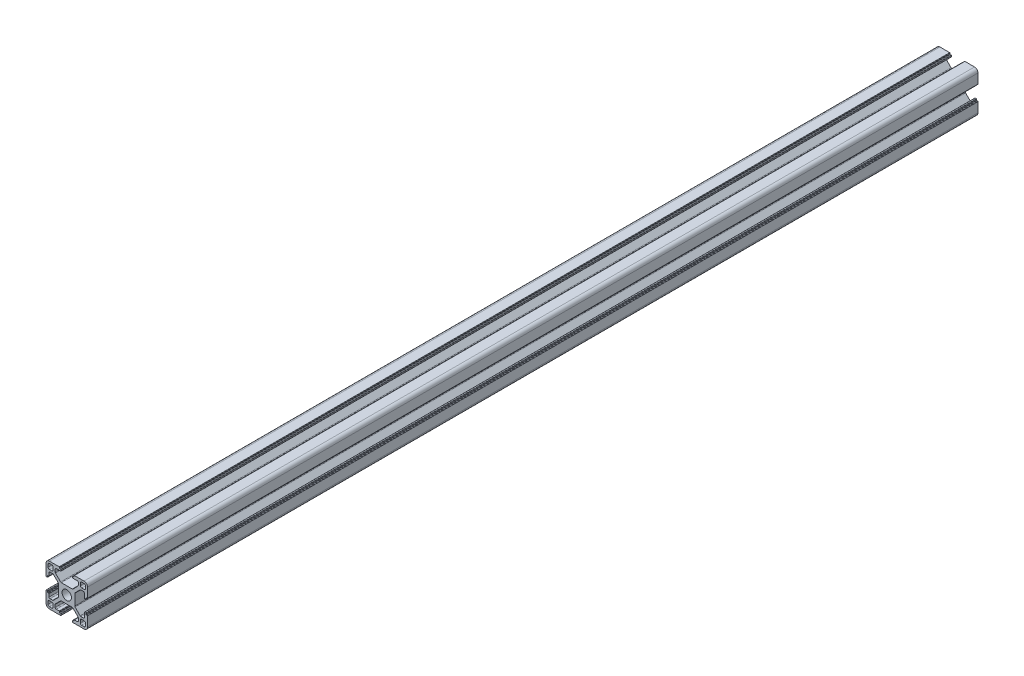
SolidWorks part; units mm, degrees
material "6063-T5"
ref_plane "Front Plane" through (0, 0, 0) normal (0, 0, 1) x (1, 0, 0)
ref_plane "Top Plane" through (0, 0, 0) normal (0, 1, 0) x (1, 0, 0)
ref_plane "Right Plane" through (0, 0, 0) normal (1, 0, 0) x (0, 0, -1)
sketch "Sketch1" plane through (0, 0, 0) normal (0, 0, 1) x (1, 0, 0)
  line L0 (0, 2.5) -> (0, 10.6)
  line L1 (2.5, 30) -> (9.5, 30)
  line L2 (30, 27.5) -> (30, 20.5)
  line L3 (27.5, 0) -> (19.4, 0)
  line L4 (19.464, 9.1128) -> (23.1303, 5.4465)
  line L5 (21.0197, 10.536) -> (24.686, 6.8697)
  line L6 (10.536, 21.0197) -> (6.8697, 24.686)
  line L7 (8.9803, 19.464) -> (5.314, 23.1303)
  line L8 (11.0663, 20.8) -> (18.9337, 20.8)
  line L9 (20.8, 18.9337) -> (20.8, 11.0663)
  line L10 (18.9337, 9.3324) -> (11.0663, 9.3324)
  line L11 (9.2, 11.0663) -> (9.2, 18.9337)
  line L12 (0, 19.4) -> (0, 27.5)
  line L13 (30, 9.5) -> (30, 2.5)
  line L14 (19.4, 27.8) -> (22.6, 27.8)
  line L15 (10.6, 27.8) -> (7.4, 27.8)
  line L16 (10.6, 0) -> (2.5, 0)
  line L17 (2.2, 20.5) -> (2.2, 22.6)
  line L18 (2.2, 9.5) -> (2.2, 7.4)
  line L19 (9.5, 2.3324) -> (7.4, 2.3324)
  line L20 (19.464, 21.0197) -> (23.1303, 24.686)
  line L21 (21.0197, 19.464) -> (24.686, 23.1303)
  line L22 (8.9803, 10.536) -> (5.314, 6.8697)
  line L23 (10.536, 9.1128) -> (6.8697, 5.4465)
  line L24 (10.8, 28.8) -> (10.8, 28)
  line L25 (19.2, 28.8) -> (19.2, 28)
  line L26 (0.2, 19.2) -> (1, 19.2)
  line L27 (0.2, 10.8) -> (1, 10.8)
  line L28 (28.8, 19.2) -> (28, 19.2)
  line L29 (28.8, 10.8) -> (28, 10.8)
  line L30 (10.8, 0.2) -> (10.8, 1.1324)
  line L31 (19.2, 0.2) -> (19.2, 1.1324)
  line L32 (20.5, 30) -> (27.5, 30)
  line L33 (27.8, 19.4) -> (27.8, 22.6)
  line L34 (27.8, 10.6) -> (27.8, 7.4)
  line L35 (20.5, 2.2) -> (22.6, 2.2)
  line L36 (6.65, 27.05) -> (6.65, 25.2163)
  line L37 (23.35, 27.05) -> (23.35, 25.2163)
  line L38 (2.95, 23.35) -> (4.7837, 23.35)
  line L39 (27.05, 23.35) -> (25.2163, 23.35)
  line L40 (2.95, 6.65) -> (4.7837, 6.65)
  line L41 (6.65, 3.0824) -> (6.65, 4.9161)
  line L42 (23.35, 2.95) -> (23.35, 4.9161)
  line L43 (27.05, 6.65) -> (25.2163, 6.65)
  line L44 (29, 10.6) -> (29, 9.9)
  line L45 (29.8, 20.3) -> (29.2, 20.3)
  line L46 (29, 20.1) -> (29, 19.4)
  line L47 (29.2, 9.7) -> (29.8, 9.7)
  line L48 (19.4, 29) -> (20.1, 29)
  line L49 (9.7, 29.8) -> (9.7, 29.2)
  line L50 (9.9, 29) -> (10.6, 29)
  line L51 (20.3, 29.2) -> (20.3, 29.8)
  line L52 (9.7, 2.1324) -> (9.7, 1.5324)
  line L53 (9.9, 1.3324) -> (10.6, 1.3324)
  line L54 (19.4, 1.3324) -> (20.1, 1.3324)
  line L55 (20.3, 1.5324) -> (20.3, 2)
  line L56 (2, 20.3) -> (1.4, 20.3)
  line L57 (1.2, 20.1) -> (1.2, 19.4)
  line L58 (1.2, 10.6) -> (1.2, 9.9)
  line L59 (1.4, 9.7) -> (2, 9.7)
  line L60 (27.55, 1.45) -> (25.8, 1.45)
  line L61 (24.8, 2.45) -> (24.8, 4.2)
  line L62 (25.8, 5.2) -> (27.55, 5.2)
  line L63 (28.55, 4.2) -> (28.55, 2.45)
  line L64 (24.8, 25.8) -> (24.8, 27.55)
  line L65 (25.8, 28.55) -> (27.55, 28.55)
  line L66 (28.55, 27.55) -> (28.55, 25.8)
  line L67 (27.55, 24.8) -> (25.8, 24.8)
  line L68 (2.45, 28.55) -> (4.2, 28.55)
  line L69 (5.2, 27.55) -> (5.2, 25.8)
  line L70 (1.45, 2.45) -> (1.45, 4.2)
  line L71 (2.45, 5.2) -> (4.2, 5.2)
  line L72 (5.2, 4.2) -> (5.2, 2.45)
  line L73 (4.2, 1.45) -> (2.45, 1.45)
  line L74 (4.2, 24.8) -> (2.45, 24.8)
  line L75 (1.45, 25.8) -> (1.45, 27.55)
  circle A0 centre (15, 15) radius 3.4
  arc A1 (25.8, 1.45) -> (24.8, 2.45) centre (25.8, 2.45) cw
  arc A2 (27.55, 1.45) -> (28.55, 2.45) centre (27.55, 2.45) ccw
  arc A3 (27.55, 5.2) -> (28.55, 4.2) centre (27.55, 4.2) cw
  arc A4 (24.8, 4.2) -> (25.8, 5.2) centre (25.8, 4.2) cw
  arc A5 (1.45, 2.45) -> (2.45, 1.45) centre (2.45, 2.45) ccw
  arc A6 (5.2, 2.45) -> (4.2, 1.45) centre (4.2, 2.45) cw
  arc A7 (4.2, 5.2) -> (5.2, 4.2) centre (4.2, 4.2) cw
  arc A8 (1.45, 4.2) -> (2.45, 5.2) centre (2.45, 4.2) cw
  arc A9 (24.8, 25.8) -> (25.8, 24.8) centre (25.8, 25.8) ccw
  arc A10 (28.55, 25.8) -> (27.55, 24.8) centre (27.55, 25.8) cw
  arc A11 (27.55, 28.55) -> (28.55, 27.55) centre (27.55, 27.55) cw
  arc A12 (24.8, 27.55) -> (25.8, 28.55) centre (25.8, 27.55) cw
  arc A13 (4.2, 28.55) -> (5.2, 27.55) centre (4.2, 27.55) cw
  arc A14 (5.2, 25.8) -> (4.2, 24.8) centre (4.2, 25.8) cw
  arc A15 (2.45, 24.8) -> (1.45, 25.8) centre (2.45, 25.8) cw
  arc A16 (2.45, 28.55) -> (1.45, 27.55) centre (2.45, 27.55) ccw
  arc A17 (30, 2.5) -> (27.5, 0) centre (27.5, 2.5) cw
  arc A18 (0, 2.5) -> (2.5, 0) centre (2.5, 2.5) ccw
  arc A19 (27.5, 30) -> (30, 27.5) centre (27.5, 27.5) cw
  arc A20 (0, 27.5) -> (2.5, 30) centre (2.5, 27.5) cw
  arc A21 (0, 10.6) -> (0.2, 10.8) centre (0.2, 10.6) cw
  arc A22 (1.2, 10.6) -> (1, 10.8) centre (1, 10.6) ccw
  arc A23 (2, 9.7) -> (2.2, 9.5) centre (2, 9.5) cw
  arc A24 (9.7, 2.1324) -> (9.5, 2.3324) centre (9.5, 2.1324) ccw
  arc A25 (10.6, 1.3324) -> (10.8, 1.1324) centre (10.6, 1.1324) cw
  arc A26 (10.6, 0) -> (10.8, 0.2) centre (10.6, 0.2) ccw
  arc A27 (19.4, 0) -> (19.2, 0.2) centre (19.4, 0.2) cw
  arc A28 (19.4, 1.3324) -> (19.2, 1.1324) centre (19.4, 1.1324) ccw
  arc A29 (20.3, 2) -> (20.5, 2.2) centre (20.5, 2) cw
  arc A30 (28, 10.8) -> (27.8, 10.6) centre (28, 10.6) ccw
  arc A31 (29, 10.6) -> (28.8, 10.8) centre (28.8, 10.6) ccw
  arc A32 (29.8, 9.7) -> (30, 9.5) centre (29.8, 9.5) cw
  arc A33 (28, 19.2) -> (27.8, 19.4) centre (28, 19.4) cw
  arc A34 (29, 19.4) -> (28.8, 19.2) centre (28.8, 19.4) cw
  arc A35 (30, 20.5) -> (29.8, 20.3) centre (29.8, 20.5) cw
  arc A36 (20.3, 29.8) -> (20.5, 30) centre (20.5, 29.8) cw
  arc A37 (19.4, 29) -> (19.2, 28.8) centre (19.4, 28.8) ccw
  arc A38 (19.2, 28) -> (19.4, 27.8) centre (19.4, 28) ccw
  arc A39 (10.8, 28) -> (10.6, 27.8) centre (10.6, 28) cw
  arc A40 (0, 19.4) -> (0.2, 19.2) centre (0.2, 19.4) ccw
  arc A41 (1.2, 19.4) -> (1, 19.2) centre (1, 19.4) cw
  arc A42 (2, 20.3) -> (2.2, 20.5) centre (2, 20.5) ccw
  arc A43 (10.6, 29) -> (10.8, 28.8) centre (10.6, 28.8) cw
  arc A44 (9.5, 30) -> (9.7, 29.8) centre (9.5, 29.8) cw
  arc A45 (1.4, 20.3) -> (1.2, 20.1) centre (1.4, 20.1) ccw
  arc A46 (20.1, 29) -> (20.3, 29.2) centre (20.1, 29.2) ccw
  arc A47 (9.7, 29.2) -> (9.9, 29) centre (9.9, 29.2) ccw
  arc A48 (29.2, 20.3) -> (29, 20.1) centre (29.2, 20.1) ccw
  arc A49 (29, 9.9) -> (29.2, 9.7) centre (29.2, 9.9) ccw
  arc A50 (20.1, 1.3324) -> (20.3, 1.5324) centre (20.1, 1.5324) ccw
  arc A51 (1.2, 9.9) -> (1.4, 9.7) centre (1.4, 9.9) ccw
  arc A52 (9.7, 1.5324) -> (9.9, 1.3324) centre (9.9, 1.5324) ccw
  arc A53 (23.35, 25.2163) -> (23.1303, 24.686) centre (22.6, 25.2163) cw
  arc A54 (25.2163, 23.35) -> (24.686, 23.1303) centre (25.2163, 22.6) ccw
  arc A55 (20.8, 18.9337) -> (21.0197, 19.464) centre (21.55, 18.9337) cw
  arc A56 (18.9337, 20.8) -> (19.464, 21.0197) centre (18.9337, 21.55) ccw
  arc A57 (6.65, 25.2163) -> (6.8697, 24.686) centre (7.4, 25.2163) ccw
  arc A58 (11.0663, 20.8) -> (10.536, 21.0197) centre (11.0663, 21.55) cw
  arc A59 (4.7837, 23.35) -> (5.314, 23.1303) centre (4.7837, 22.6) cw
  arc A60 (9.2, 18.9337) -> (8.9803, 19.464) centre (8.45, 18.9337) ccw
  arc A61 (4.7837, 6.65) -> (5.314, 6.8697) centre (4.7837, 7.4) ccw
  arc A62 (9.2, 11.0663) -> (8.9803, 10.536) centre (8.45, 11.0663) cw
  arc A63 (6.65, 4.9161) -> (6.8697, 5.4465) centre (7.4, 4.9161) cw
  arc A64 (11.0663, 9.3324) -> (10.536, 9.1128) centre (11.0663, 8.5824) ccw
  arc A65 (18.9337, 9.3324) -> (19.464, 9.1128) centre (18.9337, 8.5824) cw
  arc A66 (20.8, 11.0663) -> (21.0197, 10.536) centre (21.55, 11.0663) ccw
  arc A67 (25.2163, 6.65) -> (24.686, 6.8697) centre (25.2163, 7.4) cw
  arc A68 (23.35, 4.9161) -> (23.1303, 5.4465) centre (22.6, 4.9161) ccw
  arc A69 (7.4, 2.3324) -> (6.65, 3.0824) centre (7.4, 3.0824) cw
  arc A70 (22.6, 2.2) -> (23.35, 2.95) centre (22.6, 2.95) ccw
  arc A71 (27.8, 7.4) -> (27.05, 6.65) centre (27.05, 7.4) cw
  arc A72 (27.8, 22.6) -> (27.05, 23.35) centre (27.05, 22.6) ccw
  arc A73 (22.6, 27.8) -> (23.35, 27.05) centre (22.6, 27.05) cw
  arc A74 (2.2, 7.4) -> (2.95, 6.65) centre (2.95, 7.4) ccw
  arc A75 (2.2, 22.6) -> (2.95, 23.35) centre (2.95, 22.6) cw
  arc A76 (7.4, 27.8) -> (6.65, 27.05) centre (7.4, 27.05) ccw
  point P115 (0, 0)
extrude "Boss-Extrude1" add sketch "Sketch1" along normal blind 644
